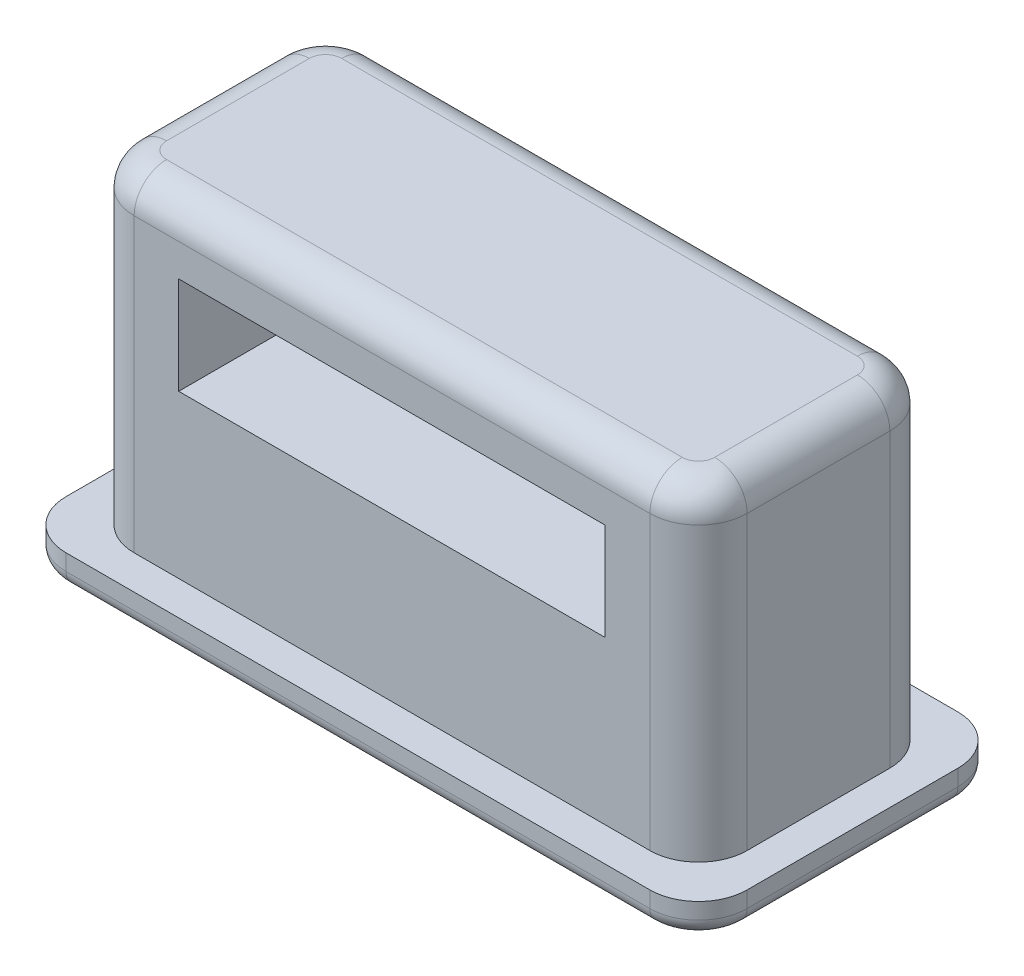
SolidWorks part; units mm, degrees
ref_plane "Front Plane" through (0, 0, 0) normal (0, 0, 1) x (1, 0, 0)
ref_plane "Top Plane" through (0, 0, 0) normal (0, 1, 0) x (1, 0, 0)
ref_plane "Right Plane" through (0, 0, 0) normal (1, 0, 0) x (0, 0, -1)
sketch "Sketch1" plane through (0, 0, 0) normal (0, 1, 0) x (1, 0, 0)
  line L1 (-56.7477, 15.4606) -> (-14.7477, 15.4606)
  line L2 (-56.7477, 15.4606) -> (-56.7477, -3.5394)
  line L3 (-56.7477, -3.5394) -> (-14.7477, -3.5394)
  line L4 (-14.7477, 15.4606) -> (-14.7477, -3.5394)
  dimension "D1" = 42
  dimension "D2" = 19
extrude "Boss-Extrude1" add sketch "Sketch1" along normal blind 2
fillet "Fillet1" radius 3 4 edges at (-56.7477, 1, -15.4606) (-56.7477, 1, 3.5394) (-14.7477, 1, -15.4606) (-14.7477, 1, 3.5394)
fillet "Fillet2" radius 1 8 edges at (-55.869, 0, 2.6607) (-56.7477, 0, -5.9606) (-55.869, 0, -14.5819) (-35.7477, 0, -15.4606) (-15.6264, 0, -14.5819) (-14.7477, 0, -5.9606) (-15.6264, 0, 2.6607) (-35.7477, 0, 3.5394)
sketch "Sketch2" plane through (0, 2, 0) normal (0, 1, 0) x (1, 0, 0)
  line L0 (-17.7477, 15.4606) -> (-53.7477, 15.4606) construction
  line L1 (-54.6477, 13.3606) -> (-16.8477, 13.3606)
  line L2 (-54.6477, 13.3606) -> (-54.6477, -1.4394)
  line L3 (-54.6477, -1.4394) -> (-16.8477, -1.4394)
  line L4 (-16.8477, 13.3606) -> (-16.8477, -1.4394)
  line L5 (-56.7477, 12.4606) -> (-56.7477, -0.5394) construction
  dimension "D1" = 37.8
  dimension "D2" = 14.8
  dimension "D3" = 2.1
  dimension "D4" = 2.1
extrude "Boss-Extrude2" add sketch "Sketch2" along normal blind 10
sketch "Sketch3" plane through (0, 12, 0) normal (0, 1, 0) x (1, 0, 0)
  line L0 (-48.8977, 13.3606) -> (-48.8977, -1.4394) construction
  line L1 (-16.8477, 13.3606) -> (-54.6477, 13.3606) construction
  line L2 (-54.6477, -1.4394) -> (-16.8477, -1.4394) construction
  line L3 (-54.6477, 13.3606) -> (-54.6477, -1.4394) construction
  line L4 (-22.5977, 13.3606) -> (-22.5977, -1.4394) construction
  line L5 (-16.8477, -1.4394) -> (-16.8477, 13.3606) construction
  line L9 (-22.5977, 13.3606) -> (-16.8477, 13.3606)
  line L10 (-22.5977, 13.3606) -> (-22.5977, -1.4394)
  line L11 (-22.5977, -1.4394) -> (-16.8477, -1.4394)
  line L12 (-16.8477, 13.3606) -> (-16.8477, -1.4394)
  line L13 (-54.6477, 13.3606) -> (-48.8977, 13.3606)
  line L14 (-54.6477, 13.3606) -> (-54.6477, -1.4394)
  line L15 (-54.6477, -1.4394) -> (-48.8977, -1.4394)
  line L16 (-48.8977, 13.3606) -> (-48.8977, -1.4394)
  dimension "D1" = 5.75
  dimension "D2" = 5.75
extrude "Boss-Extrude3" add sketch "Sketch3" along normal blind 10
sketch "Sketch5" plane through (-48.8977, 0, 0) normal (1, 0, 0) x (0, 0, -1)
  line L1 (-1.4394, 22) -> (13.3606, 22)
  line L2 (-1.4394, 22) -> (-1.4394, 18)
  line L3 (-1.4394, 18) -> (13.3606, 18)
  line L4 (13.3606, 22) -> (13.3606, 18)
  dimension "D1" = 14.8
  dimension "D2" = 4
extrude "Boss-Extrude4" add sketch "Sketch5" along normal up to surface (26.3 mm away) up to face at (-22.5977, 17, -5.9606)
fillet "Fillet4" radius 3 4 edges at (-16.8477, 12, -13.3606) (-16.8477, 12, 1.4394) (-54.6477, 12, -13.3606) (-54.6477, 12, 1.4394)
fillet "Fillet5" radius 2 8 edges at (-17.7264, 22, -12.4819) (-16.8477, 22, -5.9606) (-17.7264, 22, 0.5607) (-35.7477, 22, 1.4394) (-53.769, 22, 0.5607) (-54.6477, 22, -5.9606) (-53.769, 22, -12.4819) (-35.7477, 22, -13.3606)
